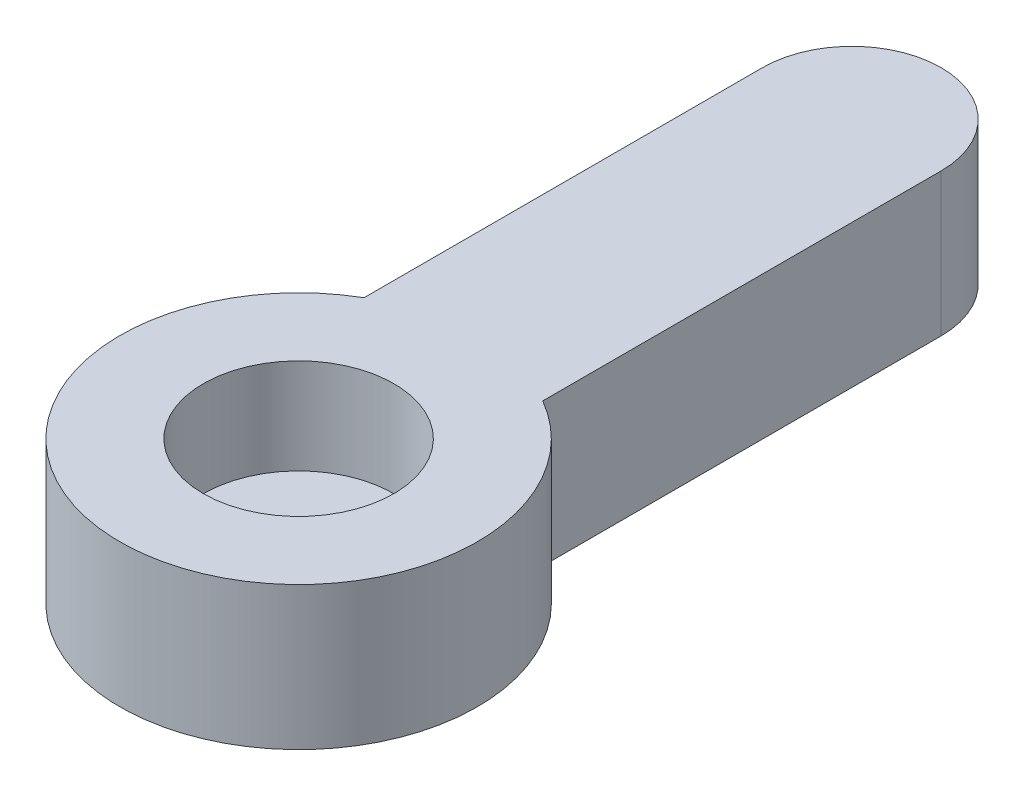
SolidWorks part; units mm, degrees
ref_plane "Front Plane" through (0, 0, 0) normal (0, 0, 1) x (1, 0, 0)
ref_plane "Top Plane" through (0, 0, 0) normal (0, 1, 0) x (1, 0, 0)
ref_plane "Right Plane" through (0, 0, 0) normal (1, 0, 0) x (0, 0, -1)
sketch "Sketch1" plane through (0, 0, 0) normal (0, 1, 0) x (1, 0, 0)
  line L0 (0, 0) -> (0, 34.5) construction
  line L1 (-3.75, 13.9952) -> (-3.75, 30.7188)
  line L2 (3.75, 13.9952) -> (3.75, 30.7188)
  arc A0 (-3.75, 13.9952) -> (3.75, 13.9952) centre (0, 7.5) ccw
  arc A1 (-3.75, 30.7188) -> (3.75, 30.7188) centre (0, 30.7188) cw
  point P7 (3.75, 22.357)
  dimension "D2" = 27
  dimension "D4" = 7.5
  dimension "D1" = 34.5
  dimension "D3" = 7.5
extrude "Boss-Extrude1" add sketch "Sketch1" along normal blind 6 contours A1 L2 A0 L1
sketch "Sketch3" plane through (0, 6, 0) normal (0, 1, 0) x (1, 0, 0)
  line L0 (0, 0) -> (0, 15.0007) construction
  line L1 (-7.5, 7.5) -> (7.5, 7.5) construction
  arc A0 (-3.75, 13.9952) -> (3.75, 13.9952) centre (0, 7.5) ccw construction
  circle A1 centre (0, 7.5003) radius 4
  dimension "D1" = 8
extrude "Cut-Extrude1" cut sketch "Sketch3" against normal blind 4
